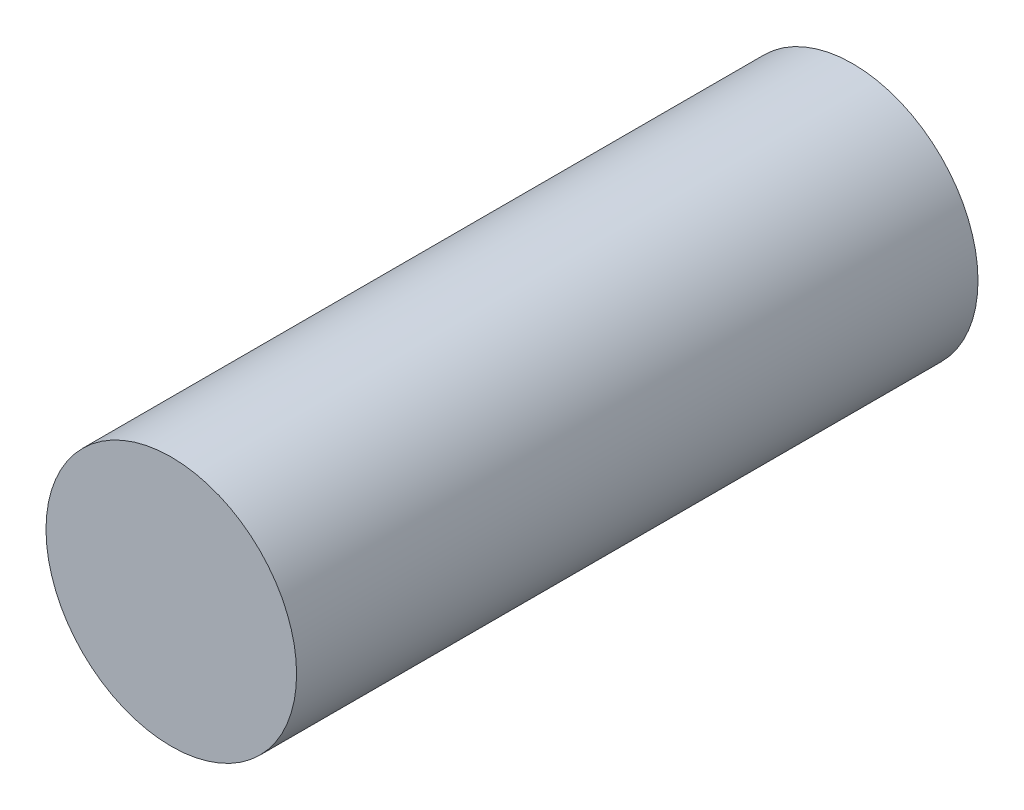
SolidWorks part; units mm, degrees
other "DetailItem1"
material "EN36A"
ref_plane "Front Plane" through (0, 0, 0) normal (0, 0, 1) x (1, 0, 0)
ref_plane "Top Plane" through (0, 0, 0) normal (0, 1, 0) x (1, 0, 0)
ref_plane "Right Plane" through (0, 0, 0) normal (1, 0, 0) x (0, 0, -1)
sketch "Sketch1" plane through (0, 0, 0) normal (0, 0, 1) x (1, 0, 0)
  circle A0 centre (0, 0) radius 7.98
  dimension "D1" = 15.96
extrude "Extrude1" add sketch "Sketch1" along normal blind 43.4
